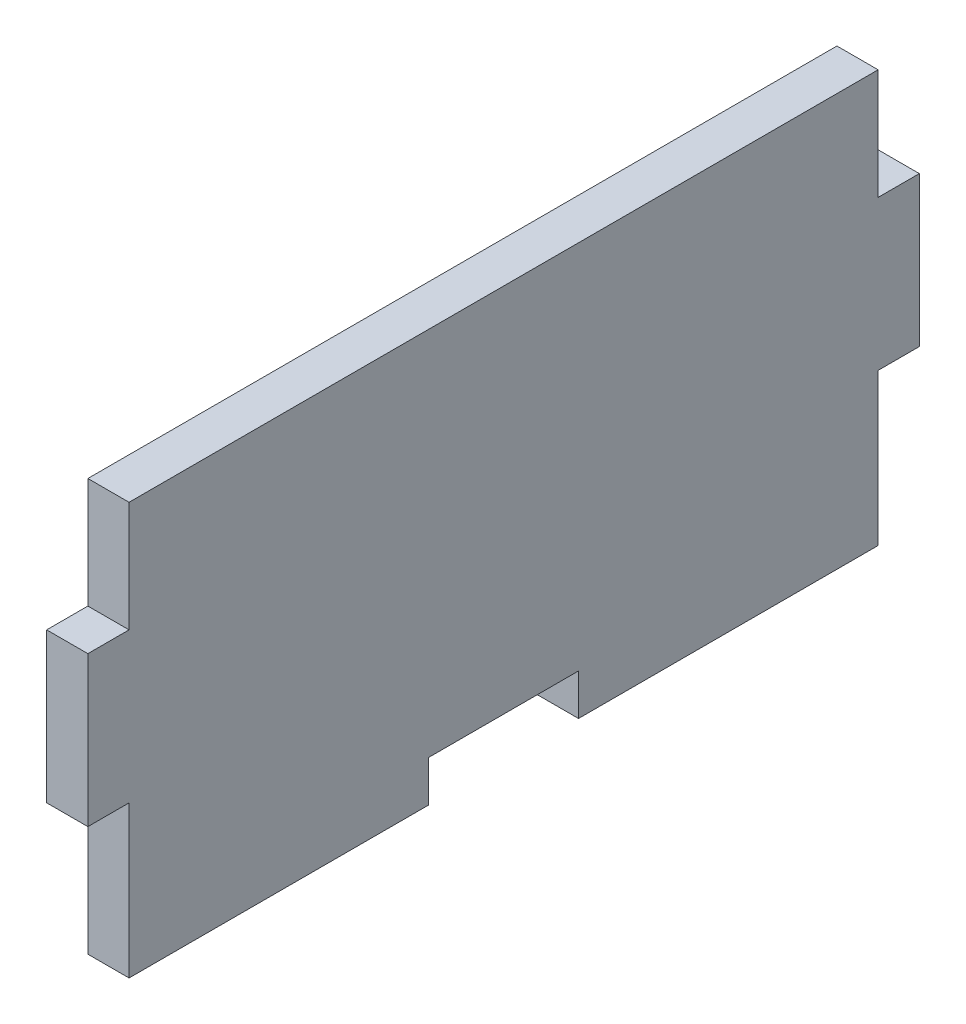
SolidWorks part; units mm, degrees
ref_plane "Front Plane" through (0, 0, 0) normal (0, 0, 1) x (1, 0, 0)
ref_plane "Top Plane" through (0, 0, 0) normal (0, 1, 0) x (1, 0, 0)
ref_plane "Right Plane" through (0, 0, 0) normal (1, 0, 0) x (0, 0, -1)
sketch "Sketch1" plane through (0, 0, 0) normal (1, 0, 0) x (0, 0, -1)
  line L8 (61.4178, 55.0371) -> (61.4178, 5.5371) construction
  line L9 (51.4178, 0.0371) -> (51.4178, 5.5371)
  line L10 (-0.5776, 30.2871) -> (84.4224, 30.2871) construction
  line L11 (111.4178, 20.2871) -> (116.9178, 20.2871)
  line L12 (71.4178, 0.0371) -> (71.4178, 5.5371)
  line L13 (116.9178, 40.2871) -> (111.4178, 40.2871)
  line L14 (5.9178, 40.2871) -> (11.4178, 40.2871)
  line L16 (11.4178, 20.2871) -> (5.9178, 20.2871)
  line L20 (111.4178, 55.0371) -> (111.4178, 40.2871)
  line L22 (11.4178, 40.2871) -> (11.4178, 55.0371)
  line L24 (11.4178, 0.0371) -> (51.4178, 0.0371)
  line L25 (5.9178, 40.2871) -> (5.9178, 20.2871)
  line L26 (116.9178, 40.2871) -> (116.9178, 20.2871)
  line L27 (71.4178, 0.0371) -> (111.4178, 0.0371)
  line L28 (11.4178, 55.0371) -> (111.4178, 55.0371)
  line L30 (51.4178, 5.5371) -> (71.4178, 5.5371)
  line L32 (111.4178, 20.2871) -> (111.4178, 0.0371)
  line L35 (51.4178, 5.5371) -> (71.4178, 5.5371) construction
  line L37 (11.4178, 20.2871) -> (11.4178, 0.0371)
  point P25 (61.4178, 30.2871)
  dimension "D1" = 5.5
  dimension "D2" = 5.5
  dimension "D4" = 20
  dimension "D5" = 10
  dimension "D6" = 20
  dimension "D7" = 10
  dimension "D8" = 55
  dimension "D9" = 5.5
extrude "Boss-Extrude1" add sketch "Sketch1" along normal blind 5.5
